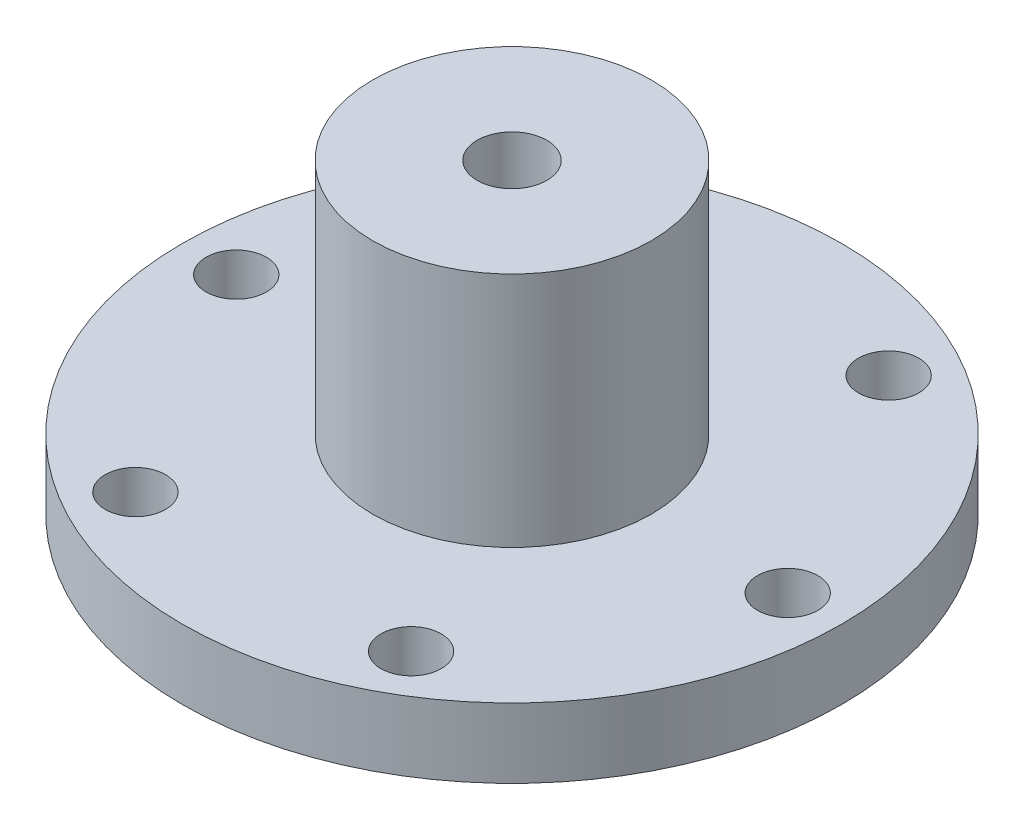
SolidWorks part; units mm, degrees
material "1060-H12"
ref_plane "Front Plane" through (0, 0, 0) normal (0, 0, 1) x (1, 0, 0)
ref_plane "Top Plane" through (0, 0, 0) normal (0, 1, 0) x (1, 0, 0)
ref_plane "Right Plane" through (0, 0, 0) normal (1, 0, 0) x (0, 0, -1)
sketch "Sketch1" plane through (0, 0, 0) normal (0, 1, 0) x (1, 0, 0)
  circle A0 centre (0, 0) radius 28.4
  dimension "D1" = 56.8
extrude "Boss-Extrude1" add sketch "Sketch1" along normal blind 6
sketch "Sketch2" plane through (0, 6, 0) normal (0, 1, 0) x (1, 0, 0)
  circle A0 centre (0, 0) radius 12
  dimension "D1" = 24
extrude "Boss-Extrude2" add sketch "Sketch2" along normal blind 20.4
sketch "Sketch3" plane through (0, 26.4, 0) normal (0, 1, 0) x (1, 0, 0)
  circle A0 centre (0, 0) radius 3
  dimension "D1" = 6
extrude "Cut-Extrude1" cut sketch "Sketch3" against normal through all
sketch "Sketch4" plane through (0, 6, 0) normal (0, 1, 0) x (1, 0, 0)
  line L0 (23.75, 0) -> (0, 0) construction
  circle A1 centre (0, 0) radius 23.75 construction
  circle A2 centre (23.75, 0) radius 2.6
  circle A3 centre (11.875, -20.5681) radius 2.6
  circle A4 centre (-11.875, -20.5681) radius 2.6
  circle A5 centre (-23.75, 0) radius 2.6
  circle A6 centre (-11.875, 20.5681) radius 2.6
  circle A7 centre (11.875, 20.5681) radius 2.6
  point P19 (0, 0)
  dimension "D1" = 47.5
  dimension "D2" = 5.2
  dimension "D3" = 6
extrude "Cut-Extrude2" cut sketch "Sketch4" against normal through all
sketch "Sketch6" plane through (0, 0, 0) normal (1, 0, 0) x (0, 0, -1)
  line L0 (12, 26.4) -> (-12, 26.4) construction
  circle A0 centre (0, 16.2) radius 1.65
  dimension "D1" = 3.3
  dimension "D2" = 10.2
extrude "Cut-Extrude3" cut sketch "Sketch6" against normal through all
